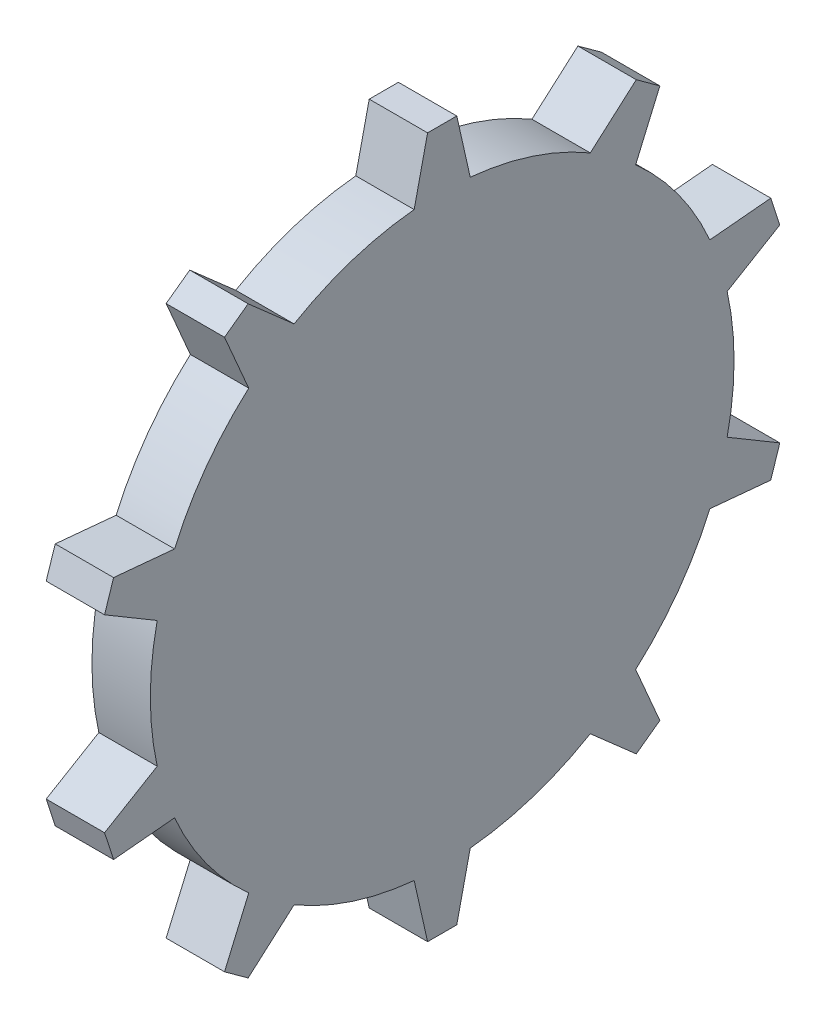
SolidWorks part; units mm, degrees
ref_plane "Спереди" through (0, 0, 0) normal (0, 0, 1) x (1, 0, 0)
ref_plane "Сверху" through (0, 0, 0) normal (0, 1, 0) x (1, 0, 0)
ref_plane "Справа" through (0, 0, 0) normal (1, 0, 0) x (0, 0, -1)
other "Configuration Table"
sketch "Эскиз1" plane through (0, 0, 0) normal (1, 0, 0) x (0, 0, -1)
  line L0 (0, 0) -> (0, 20) construction
  line L1 (0, 20) -> (0, 24) construction
  line L2 (0, 24) -> (-1, 24) construction
  line L4 (0, 24) -> (1, 24) construction
  line L5 (0.9815, 24.0824) -> (1.74, 20.711) construction
  line L7 (-1.1199, 23.4671) -> (-1.8755, 20.1087) construction
  line L8 (-1.9, 20) -> (0, 20) construction
  line L9 (0, 20) -> (1.9, 20) construction
  line L10 (-1, 24) -> (1, 24)
  line L11 (-1, 24) -> (-1.9208, 19.9075)
  line L12 (1, 24) -> (1.9208, 19.9075)
  line L13 (13.2978, 20.0042) -> (10.1474, 17.2346)
  line L14 (13.2978, 20.0042) -> (14.9159, 18.8286)
  line L15 (14.9159, 18.8286) -> (13.2553, 14.9765)
  line L16 (22.5163, 8.3675) -> (18.3396, 7.9786)
  line L17 (22.5163, 8.3675) -> (23.1344, 6.4654)
  line L18 (23.1344, 6.4654) -> (19.5268, 4.325)
  line L19 (23.1344, -6.4654) -> (19.5268, -4.325)
  line L20 (23.1344, -6.4654) -> (22.5163, -8.3675)
  line L21 (22.5163, -8.3675) -> (18.3396, -7.9786)
  line L22 (14.9159, -18.8286) -> (13.2553, -14.9765)
  line L23 (14.9159, -18.8286) -> (13.2978, -20.0042)
  line L24 (13.2978, -20.0042) -> (10.1474, -17.2346)
  line L25 (1, -24) -> (1.9208, -19.9075)
  line L26 (1, -24) -> (-1, -24)
  line L27 (-1, -24) -> (-1.9208, -19.9075)
  line L28 (-13.2978, -20.0042) -> (-10.1474, -17.2346)
  line L29 (-13.2978, -20.0042) -> (-14.9159, -18.8286)
  line L30 (-14.9159, -18.8286) -> (-13.2553, -14.9765)
  line L31 (-22.5163, -8.3675) -> (-18.3396, -7.9786)
  line L32 (-22.5163, -8.3675) -> (-23.1344, -6.4654)
  line L33 (-23.1344, -6.4654) -> (-19.5268, -4.325)
  line L34 (-23.1344, 6.4654) -> (-19.5268, 4.325)
  line L35 (-23.1344, 6.4654) -> (-22.5163, 8.3675)
  line L36 (-22.5163, 8.3675) -> (-18.3396, 7.9786)
  line L37 (-14.9159, 18.8286) -> (-13.2553, 14.9765)
  line L38 (-14.9159, 18.8286) -> (-13.2978, 20.0042)
  line L39 (-13.2978, 20.0042) -> (-10.1474, 17.2346)
  circle A0 centre (0, 0) radius 20 construction
  arc A1 (1.9208, 19.9075) -> (10.1474, 17.2346) centre (0, 0) cw
  arc A2 (13.2553, 14.9765) -> (18.3396, 7.9786) centre (0, 0) cw
  arc A3 (19.5268, 4.325) -> (19.5268, -4.325) centre (0, 0) cw
  arc A4 (18.3396, -7.9786) -> (13.2553, -14.9765) centre (0, 0) cw
  arc A5 (10.1474, -17.2346) -> (1.9208, -19.9075) centre (0, 0) cw
  arc A6 (-1.9208, -19.9075) -> (-10.1474, -17.2346) centre (0, 0) cw
  arc A7 (-13.2553, -14.9765) -> (-18.3396, -7.9786) centre (0, 0) cw
  arc A8 (-19.5268, -4.325) -> (-19.5268, 4.325) centre (0, 0) cw
  arc A9 (-18.3396, 7.9786) -> (-13.2553, 14.9765) centre (0, 0) cw
  arc A10 (-10.1474, 17.2346) -> (-1.9208, 19.9075) centre (0, 0) cw
  point P3 (0, 0)
  point P16 (0, 0)
  point P21 (0, 0)
  point P53 (0, 0)
  point P54 (1.9208, 19.9075)
  point P56 (0, 0)
  point P57 (0, 0)
  point P74 (0, 0)
  point P76 (0, 0)
  dimension "D1" = 40
  dimension "D2" = 4
  dimension "D3" = 2
  dimension "D4" = 1.9
  dimension "D5" = 1.9
  dimension "D6" = 10
  dimension "D7" = 10
extrude "Бобышка-Вытянуть1" add sketch "Эскиз1" along normal blind 4
